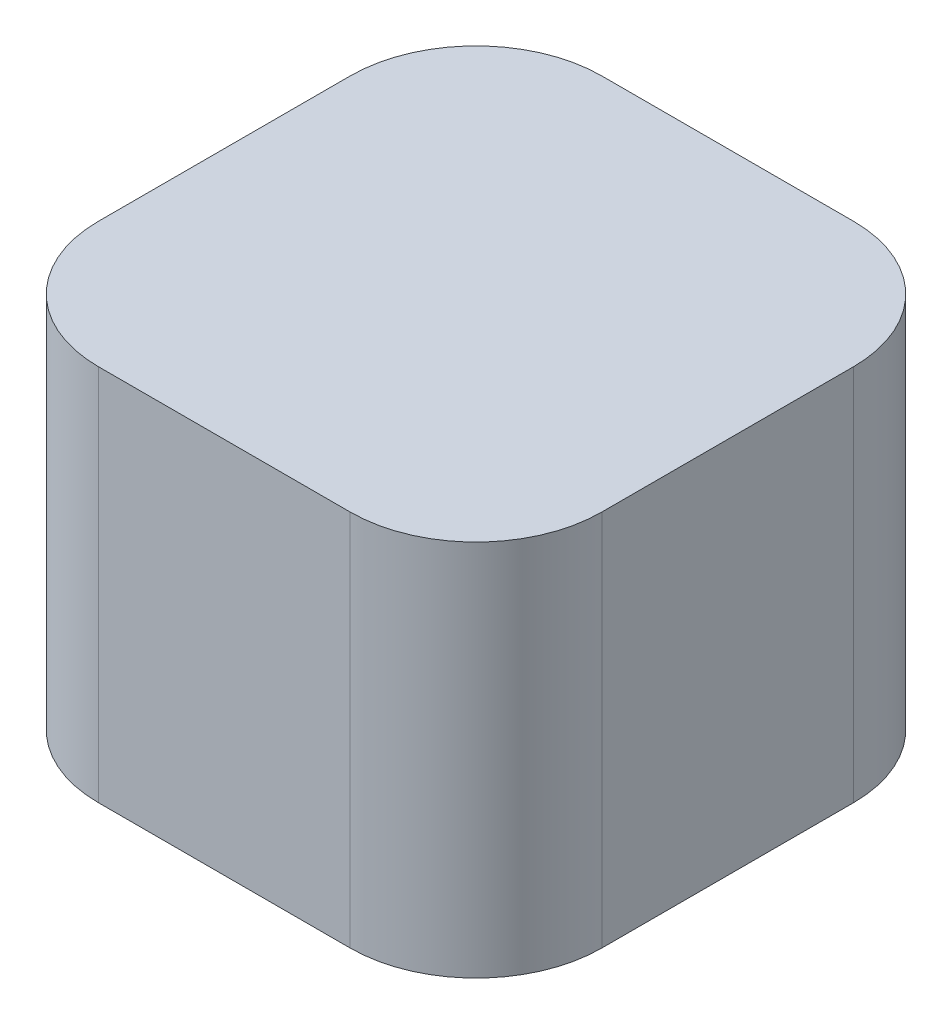
SolidWorks part; units mm, degrees
ref_plane "Front Plane" through (0, 0, 0) normal (0, 0, 1) x (1, 0, 0)
ref_plane "Top Plane" through (0, 0, 0) normal (0, 1, 0) x (1, 0, 0)
ref_plane "Right Plane" through (0, 0, 0) normal (1, 0, 0) x (0, 0, -1)
sketch "Sketch1" plane through (0, 0, 0) normal (0, 1, 0) x (1, 0, 0)
  line L1 (-20, -20) -> (20, -20)
  line L2 (-20, -20) -> (-20, 20)
  line L3 (-20, 20) -> (20, 20)
  line L4 (20, -20) -> (20, 20)
  line L5 (-20, -20) -> (20, 20) construction
  line L6 (-20, 20) -> (20, -20) construction
  point P0 (0, 0)
  dimension "D1" = 40
  dimension "D2" = 40
extrude "Boss-Extrude1" add sketch "Sketch1" along normal blind 30
sketch "Sketch2" plane through (0, 0, 0) normal (0, -1, 0) x (-1, 0, 0)
  circle A0 centre (0, 0) radius 10
  dimension "D1" = 20
extrude "Boss-Extrude2" add sketch "Sketch2" along normal blind 10
fillet "Fillet1" radius 10 4 edges at (-20, 15, -20) (20, 15, -20) (-20, 15, 20) (20, 15, 20)
